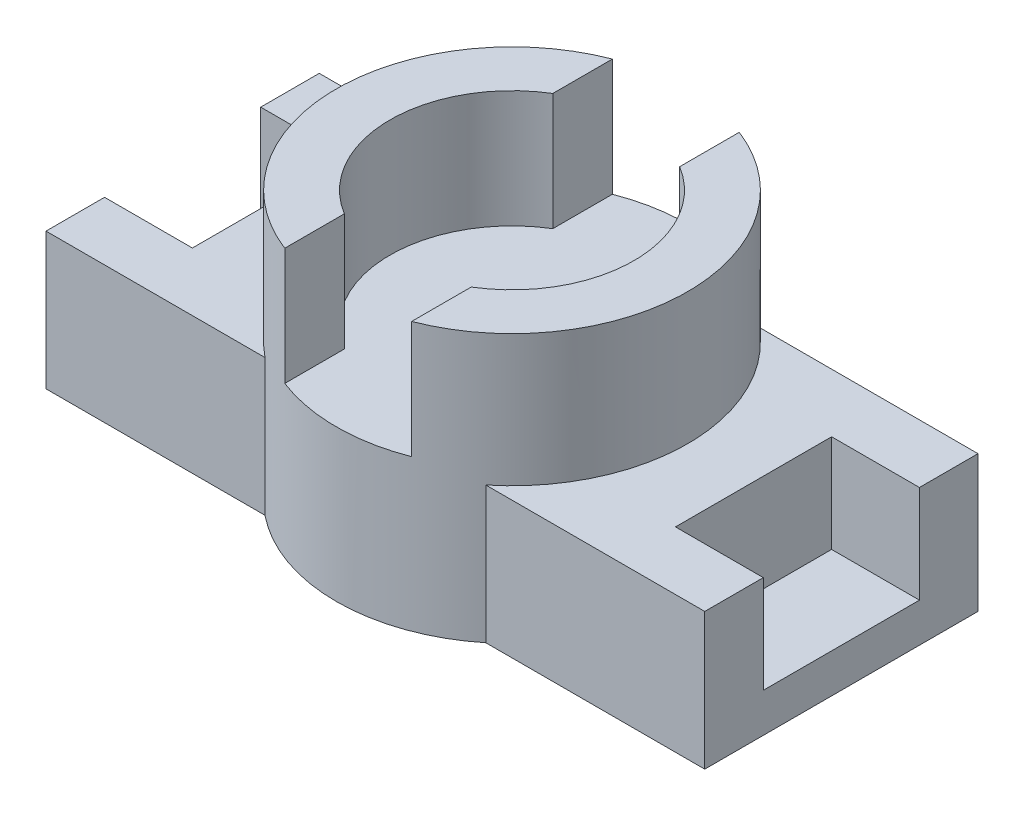
SolidWorks part; units mm, degrees
ref_plane "Front Plane" through (0, 0, 0) normal (0, 0, 1) x (1, 0, 0)
ref_plane "Top Plane" through (0, 0, 0) normal (0, 1, 0) x (1, 0, 0)
ref_plane "Right Plane" through (0, 0, 0) normal (1, 0, 0) x (0, 0, -1)
sketch "Sketch1" plane through (0, 0, 0) normal (0, 1, 0) x (1, 0, 0)
  line L1 (-67.5, -28) -> (67.5, -28)
  line L2 (-67.5, -28) -> (-67.5, 28)
  line L3 (-67.5, 28) -> (67.5, 28)
  line L4 (67.5, -28) -> (67.5, 28)
  line L5 (-67.5, -28) -> (67.5, 28) construction
  line L6 (-67.5, 28) -> (67.5, -28) construction
  point P0 (0, 0)
  dimension "D1" = 56
  dimension "D2" = 135
extrude "Boss-Extrude1" add sketch "Sketch1" along normal blind 28
sketch "Sketch2" plane through (0, 0, 0) normal (0, 1, 0) x (1, 0, 0)
  circle A0 centre (0, 0) radius 36
  dimension "D1" = 72
extrude "Boss-Extrude2" add sketch "Sketch2" along normal blind 55
sketch "Sketch3" plane through (0, 28, 0) normal (0, 1, 0) x (1, 0, 0)
  line L0 (-67.5, 28) -> (-67.5, -28) construction
  line L1 (-49.5, -16) -> (-67.5, -16)
  line L2 (-49.5, -16) -> (-49.5, 16)
  line L3 (-49.5, 16) -> (-67.5, 16)
  line L4 (-67.5, -16) -> (-67.5, 16)
  line L5 (-49.5, -16) -> (-67.5, 16) construction
  line L6 (-49.5, 16) -> (-67.5, -16) construction
  point P0 (-58.5, 0)
  point P7 (0, 0)
  point P9 (0, 0)
  dimension "D1" = 18
  dimension "D2" = 32
extrude "Cut-Extrude1" cut sketch "Sketch3" against normal blind 20
mirror "Mirror1" about plane through (0, 0, 0) normal (1, 0, 0) of "Cut-Extrude1"
sketch "Sketch4" plane through (0, 55, 0) normal (0, 1, 0) x (1, 0, 0)
  line L0 (0, 36) -> (0, -36) construction
  line L1 (-13, 33.5708) -> (-13, 21.3542)
  line L2 (13, 33.5708) -> (13, 21.3542)
  line L3 (-13, -21.3542) -> (-13, -33.5708)
  line L4 (13, -21.3542) -> (13, -33.5708)
  arc A0 (-13, 21.3542) -> (-13, -21.3542) centre (0, 0) ccw
  arc A1 (13, 33.5708) -> (-13, 33.5708) centre (0, 0) ccw
  circle A2 centre (0, 0) radius 36 construction
  arc A3 (-13, -33.5708) -> (13, -33.5708) centre (0, 0) ccw
  arc A4 (13, -21.3542) -> (13, 21.3542) centre (0, 0) ccw
  point P10 (-13, 21.3542)
  point P11 (-13, -33.5708)
  dimension "D1" = 50
  dimension "D2" = 26
extrude "Cut-Extrude2" cut sketch "Sketch4" against normal blind 24
